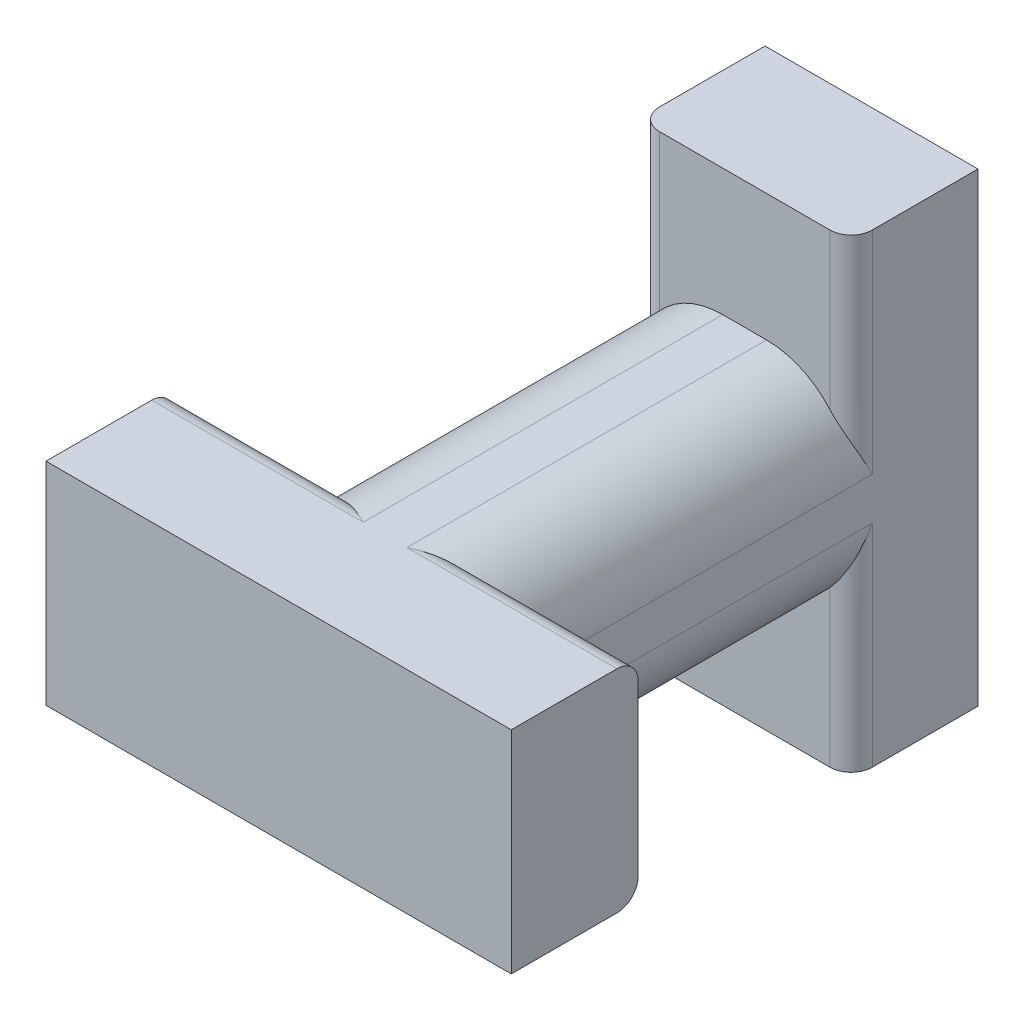
SolidWorks part; units mm, degrees
ref_plane "Plan de face" through (0, 0, 0) normal (0, 0, 1) x (1, 0, 0)
ref_plane "Plan de dessus" through (0, 0, 0) normal (0, 1, 0) x (1, 0, 0)
ref_plane "Plan de droite" through (0, 0, 0) normal (1, 0, 0) x (0, 0, -1)
sketch "Esquisse1" plane through (0, 0, 0) normal (0, 0, 1) x (1, 0, 0)
  line L0 (36.8133, 21.4816) -> (31.7782, 16.4816) construction
  line L4 (31.7782, 16.4816) -> (34.2958, 16.4816) construction
  line L5 (34.2958, 16.4816) -> (34.2958, 18.9816) construction
  line L7 (31.7782, 21.4816) -> (36.8133, 21.4816)
  line L8 (31.7782, 21.4816) -> (31.7782, 16.4816)
  line L9 (31.7782, 16.4816) -> (36.8133, 16.4816)
  line L10 (36.8133, 21.4816) -> (36.8133, 16.4816)
  line L11 (31.7782, 21.4816) -> (36.8133, 16.4816) construction
  line L12 (31.7782, 16.4816) -> (36.8133, 21.4816) construction
extrude "BASE" add sketch "Esquisse1" along normal blind 8
sketch "Esquisse4" plane through (0, 21.4816, 0) normal (0, 1, 0) x (1, 0, 0)
  line L1 (31.7782, 0) -> (36.8133, 0)
  line L2 (31.7782, 0) -> (31.7782, 3)
  line L3 (31.7782, 3) -> (36.8133, 3)
  line L4 (36.8133, 0) -> (36.8133, 3)
  dimension "D1" = 3
extrude "BOSS 1" add sketch "Esquisse4" along normal blind 3 and the other way blind 8
sketch "Esquisse5" plane through (31.7782, 0, 0) normal (-1, 0, 0) x (0, 0, 1)
  line L1 (8, 21.4816) -> (11, 21.4816)
  line L2 (8, 21.4816) -> (8, 16.4816)
  line L3 (8, 16.4816) -> (11, 16.4816)
  line L4 (11, 21.4816) -> (11, 16.4816)
  dimension "D1" = 3
extrude "BOSS 2" add sketch "Esquisse5" along normal blind 3 and the other way blind 8
fillet "CONGE MILIEU" radius 2 4 edges
fillet "CONGE HAUT ET BAS" radius 0.5 8 edges
